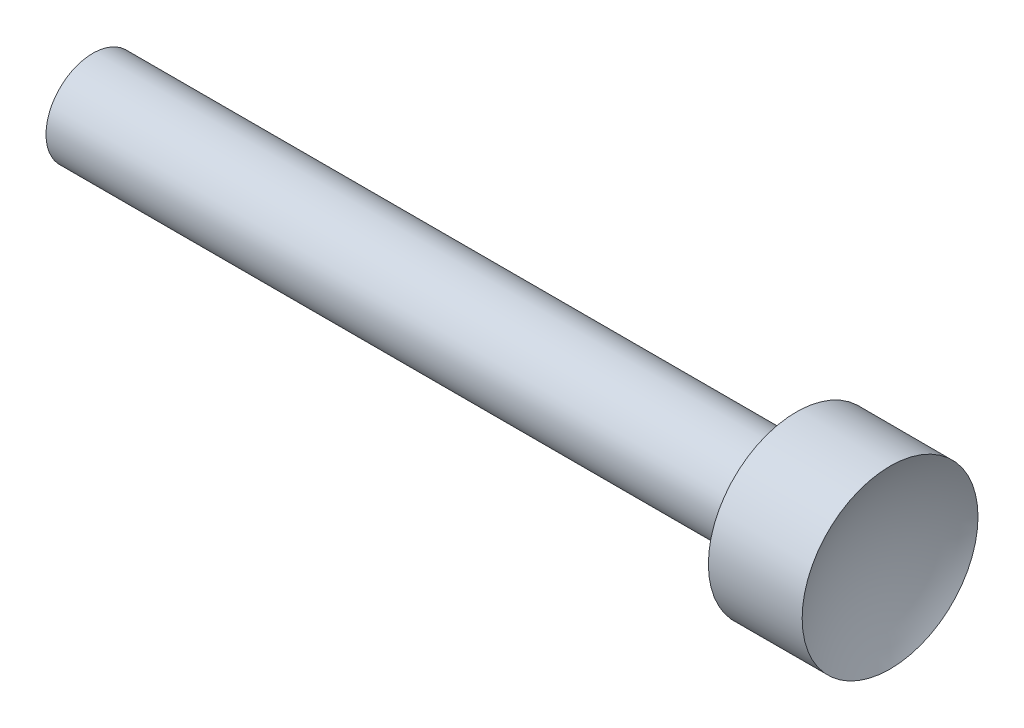
SolidWorks part; units mm, degrees
ref_plane "Front Plane" through (0, 0, 0) normal (0, 0, 1) x (1, 0, 0)
ref_plane "Top Plane" through (0, 0, 0) normal (0, 1, 0) x (1, 0, 0)
ref_plane "Right Plane" through (0, 0, 0) normal (1, 0, 0) x (0, 0, -1)
sketch "Sketch1" plane through (0, 0, 0) normal (0, 0, 1) x (1, 0, 0)
  line L8 (0, 0) -> (140.7035, 0) construction
  line L9 (66.4369, 4) -> (66.4369, 7.5)
  line L11 (6.4369, 4) -> (66.4369, 4)
  line L12 (6.4369, 4) -> (6.4369, 0)
  line L14 (66.4369, 7.5) -> (74.4369, 7.5)
  line L15 (6.4369, 0) -> (72.4273, 0)
  arc A2 (74.4369, 7.5) -> (72.4273, 0) centre (87.4273, 0) ccw
  dimension "D4" = 60
  dimension "D2" = 4
  dimension "D5" = 8
revolve "Revolve1" add sketch "Sketch1" angle 360 about L8
